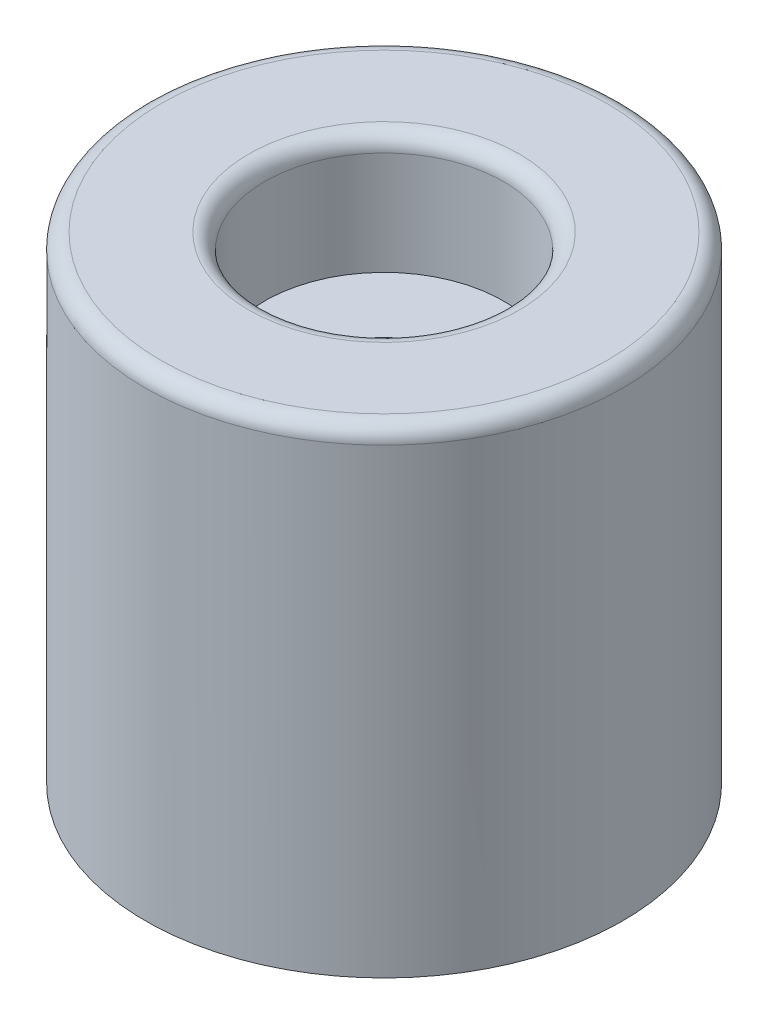
SolidWorks part; units mm, degrees
material "Rubber"
ref_plane "Front" through (0, 0, 0) normal (0, 0, 1) x (1, 0, 0)
ref_plane "Top" through (0, 0, 0) normal (0, 1, 0) x (1, 0, 0)
ref_plane "Right" through (0, 0, 0) normal (1, 0, 0) x (0, 0, -1)
sketch "Sketch1" plane through (0, 0, 0) normal (0, 1, 0) x (1, 0, 0)
  circle A0 centre (0, 0) radius 19.05
  dimension "D1" = 38.1
extrude "Boss-Extrude1" add sketch "Sketch1" along normal blind 38.1
sketch "Sketch2" plane through (0, 38.1, 0) normal (0, 1, 0) x (1, 0, 0)
  circle A0 centre (0, 0) radius 9.525
  dimension "D1" = 19.05
extrude "Cut-Extrude1" cut sketch "Sketch2" against normal blind 9.525
sketch "Sketch3" plane through (0, 28.575, 0) normal (0, 1, 0) x (1, 0, 0)
  circle A0 centre (0, 0) radius 3.175
  dimension "D1" = 6.35
extrude "Cut-Extrude2" cut sketch "Sketch3" against normal through all
fillet "Fillet1" radius 1.27 2 edges at (0, 38.1, 9.525) (0, 38.1, 19.05)
